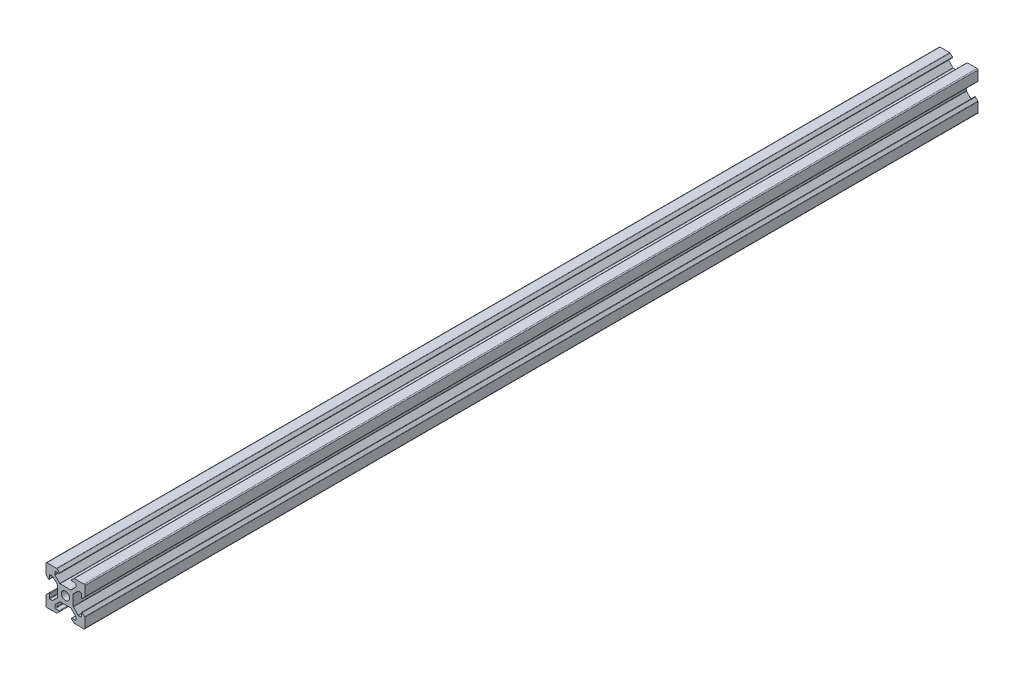
SolidWorks part; units mm, degrees
material "1060 Alloy"
ref_plane "Front Plane" through (0, 0, 0) normal (0, 0, 1) x (1, 0, 0)
ref_plane "Top Plane" through (0, 0, 0) normal (0, 1, 0) x (1, 0, 0)
ref_plane "Right Plane" through (0, 0, 0) normal (1, 0, 0) x (0, 0, -1)
sketch "Model" plane through (0, 0, 0) normal (0, 0, 1) x (1, 0, 0)
  line L0 (2012.9312, 1381.8004) -> (2012.9312, 1378.2004)
  line L1 (2016.4702, 1376.0004) -> (2017.3922, 1376.0004)
  line L2 (2020.9312, 1380.4614) -> (2020.9312, 1379.5394)
  line L3 (2016.4702, 1384.0004) -> (2017.3922, 1384.0004)
  line L270 (2012.9312, 1381.8004) -> (2012.9312, 1382.7004)
  line L271 (2012.8433, 1382.9125) -> (2010.3787, 1385.3772)
  line L272 (2010.2019, 1385.4504) -> (2008.8812, 1385.4504)
  line L273 (2008.6312, 1385.2004) -> (2008.6312, 1383.3504)
  line L274 (2008.2044, 1383.1736) -> (2007.0191, 1384.359)
  line L275 (2006.9312, 1384.5711) -> (2006.9312, 1389.5004)
  line L276 (2007.4312, 1390.0004) -> (2012.3605, 1390.0004)
  line L277 (2012.5726, 1389.9125) -> (2013.758, 1388.7272)
  line L278 (2013.5812, 1388.3004) -> (2011.7312, 1388.3004)
  line L279 (2011.4812, 1388.0504) -> (2011.4812, 1386.7297)
  line L280 (2011.5544, 1386.5529) -> (2014.0338, 1384.0736)
  line L281 (2014.2105, 1384.0004) -> (2016.4702, 1384.0004)
  line L282 (2017.3922, 1384.0004) -> (2019.6519, 1384.0004)
  line L283 (2019.8287, 1384.0736) -> (2022.308, 1386.5529)
  line L284 (2022.3812, 1386.7297) -> (2022.3812, 1388.0504)
  line L285 (2022.1312, 1388.3004) -> (2020.2812, 1388.3004)
  line L286 (2020.1044, 1388.7272) -> (2021.2898, 1389.9125)
  line L287 (2021.5019, 1390.0004) -> (2026.4312, 1390.0004)
  line L288 (2026.9312, 1389.5004) -> (2026.9312, 1384.5711)
  line L289 (2026.8433, 1384.359) -> (2025.658, 1383.1736)
  line L290 (2025.2312, 1383.3504) -> (2025.2312, 1385.2004)
  line L291 (2024.9812, 1385.4504) -> (2023.6605, 1385.4504)
  line L292 (2023.4838, 1385.3772) -> (2021.0044, 1382.8978)
  line L293 (2020.9312, 1382.7211) -> (2020.9312, 1380.4614)
  line L294 (2020.9312, 1379.5394) -> (2020.9312, 1377.2797)
  line L295 (2021.0044, 1377.1029) -> (2023.4838, 1374.6236)
  line L296 (2023.6605, 1374.5504) -> (2024.9812, 1374.5504)
  line L297 (2025.2312, 1374.8004) -> (2025.2312, 1376.6504)
  line L298 (2025.658, 1376.8272) -> (2026.8433, 1375.6418)
  line L299 (2026.9312, 1375.4297) -> (2026.9312, 1370.5004)
  line L300 (2026.4312, 1370.0004) -> (2021.5019, 1370.0004)
  line L301 (2021.2898, 1370.0883) -> (2020.1044, 1371.2736)
  line L302 (2020.2812, 1371.7004) -> (2022.1312, 1371.7004)
  line L303 (2022.3812, 1371.9504) -> (2022.3812, 1373.2711)
  line L304 (2022.308, 1373.4478) -> (2019.8287, 1375.9272)
  line L305 (2019.6519, 1376.0004) -> (2017.3922, 1376.0004)
  line L306 (2016.4702, 1376.0004) -> (2014.2105, 1376.0004)
  line L307 (2014.0338, 1375.9272) -> (2011.5544, 1373.4478)
  line L308 (2011.4812, 1373.2711) -> (2011.4812, 1371.9504)
  line L309 (2011.7312, 1371.7004) -> (2013.5812, 1371.7004)
  line L310 (2013.758, 1371.2736) -> (2012.5726, 1370.0883)
  line L311 (2012.3605, 1370.0004) -> (2007.4312, 1370.0004)
  line L312 (2006.9312, 1370.5004) -> (2006.9312, 1375.4297)
  line L313 (2007.0191, 1375.6418) -> (2008.2044, 1376.8272)
  line L314 (2008.6312, 1376.6504) -> (2008.6312, 1374.8004)
  line L315 (2008.8812, 1374.5504) -> (2010.2019, 1374.5504)
  line L316 (2010.3787, 1374.6236) -> (2012.8433, 1377.0883)
  line L317 (2012.9312, 1377.3004) -> (2012.9312, 1378.2004)
  circle A0 centre (2016.9312, 1380.0004) radius 2.1
  arc A427 (2012.9312, 1382.7004) -> (2012.8433, 1382.9125) centre (2012.6312, 1382.7004) ccw
  arc A428 (2010.3787, 1385.3772) -> (2010.2019, 1385.4504) centre (2010.2019, 1385.2004) ccw
  arc A429 (2008.8812, 1385.4504) -> (2008.6312, 1385.2004) centre (2008.8812, 1385.2004) ccw
  arc A430 (2008.2044, 1383.1736) -> (2008.6312, 1383.3504) centre (2008.3812, 1383.3504) ccw
  arc A431 (2006.9312, 1384.5711) -> (2007.0191, 1384.359) centre (2007.2312, 1384.5711) ccw
  arc A432 (2007.4312, 1390.0004) -> (2006.9312, 1389.5004) centre (2007.4312, 1389.5004) ccw
  arc A433 (2012.5726, 1389.9125) -> (2012.3605, 1390.0004) centre (2012.3605, 1389.7004) ccw
  arc A434 (2013.5812, 1388.3004) -> (2013.758, 1388.7272) centre (2013.5812, 1388.5504) ccw
  arc A435 (2011.7312, 1388.3004) -> (2011.4812, 1388.0504) centre (2011.7312, 1388.0504) ccw
  arc A436 (2011.4812, 1386.7297) -> (2011.5544, 1386.5529) centre (2011.7312, 1386.7297) ccw
  arc A437 (2014.0338, 1384.0736) -> (2014.2105, 1384.0004) centre (2014.2105, 1384.2504) ccw
  arc A441 (2019.6519, 1384.0004) -> (2019.8287, 1384.0736) centre (2019.6519, 1384.2504) ccw
  arc A442 (2022.308, 1386.5529) -> (2022.3812, 1386.7297) centre (2022.1312, 1386.7297) ccw
  arc A443 (2022.3812, 1388.0504) -> (2022.1312, 1388.3004) centre (2022.1312, 1388.0504) ccw
  arc A444 (2020.1044, 1388.7272) -> (2020.2812, 1388.3004) centre (2020.2812, 1388.5504) ccw
  arc A445 (2021.5019, 1390.0004) -> (2021.2898, 1389.9125) centre (2021.5019, 1389.7004) ccw
  arc A446 (2026.9312, 1389.5004) -> (2026.4312, 1390.0004) centre (2026.4312, 1389.5004) ccw
  arc A447 (2026.8433, 1384.359) -> (2026.9312, 1384.5711) centre (2026.6312, 1384.5711) ccw
  arc A448 (2025.2312, 1383.3504) -> (2025.658, 1383.1736) centre (2025.4812, 1383.3504) ccw
  arc A449 (2025.2312, 1385.2004) -> (2024.9812, 1385.4504) centre (2024.9812, 1385.2004) ccw
  arc A450 (2023.6605, 1385.4504) -> (2023.4838, 1385.3772) centre (2023.6605, 1385.2004) ccw
  arc A451 (2021.0044, 1382.8978) -> (2020.9312, 1382.7211) centre (2021.1812, 1382.7211) ccw
  arc A455 (2020.9312, 1377.2797) -> (2021.0044, 1377.1029) centre (2021.1812, 1377.2797) ccw
  arc A456 (2023.4838, 1374.6236) -> (2023.6605, 1374.5504) centre (2023.6605, 1374.8004) ccw
  arc A457 (2024.9812, 1374.5504) -> (2025.2312, 1374.8004) centre (2024.9812, 1374.8004) ccw
  arc A458 (2025.658, 1376.8272) -> (2025.2312, 1376.6504) centre (2025.4812, 1376.6504) ccw
  arc A459 (2026.9312, 1375.4297) -> (2026.8433, 1375.6418) centre (2026.6312, 1375.4297) ccw
  arc A460 (2026.4312, 1370.0004) -> (2026.9312, 1370.5004) centre (2026.4312, 1370.5004) ccw
  arc A461 (2021.2898, 1370.0883) -> (2021.5019, 1370.0004) centre (2021.5019, 1370.3004) ccw
  arc A462 (2020.2812, 1371.7004) -> (2020.1044, 1371.2736) centre (2020.2812, 1371.4504) ccw
  arc A463 (2022.1312, 1371.7004) -> (2022.3812, 1371.9504) centre (2022.1312, 1371.9504) ccw
  arc A464 (2022.3812, 1373.2711) -> (2022.308, 1373.4478) centre (2022.1312, 1373.2711) ccw
  arc A465 (2019.8287, 1375.9272) -> (2019.6519, 1376.0004) centre (2019.6519, 1375.7504) ccw
  arc A469 (2014.2105, 1376.0004) -> (2014.0338, 1375.9272) centre (2014.2105, 1375.7504) ccw
  arc A470 (2011.5544, 1373.4478) -> (2011.4812, 1373.2711) centre (2011.7312, 1373.2711) ccw
  arc A471 (2011.4812, 1371.9504) -> (2011.7312, 1371.7004) centre (2011.7312, 1371.9504) ccw
  arc A472 (2013.758, 1371.2736) -> (2013.5812, 1371.7004) centre (2013.5812, 1371.4504) ccw
  arc A473 (2012.3605, 1370.0004) -> (2012.5726, 1370.0883) centre (2012.3605, 1370.3004) ccw
  arc A474 (2006.9312, 1370.5004) -> (2007.4312, 1370.0004) centre (2007.4312, 1370.5004) ccw
  arc A475 (2007.0191, 1375.6418) -> (2006.9312, 1375.4297) centre (2007.2312, 1375.4297) ccw
  arc A476 (2008.6312, 1376.6504) -> (2008.2044, 1376.8272) centre (2008.3812, 1376.6504) ccw
  arc A477 (2008.6312, 1374.8004) -> (2008.8812, 1374.5504) centre (2008.8812, 1374.8004) ccw
  arc A478 (2010.2019, 1374.5504) -> (2010.3787, 1374.6236) centre (2010.2019, 1374.8004) ccw
  arc A479 (2012.8433, 1377.0883) -> (2012.9312, 1377.3004) centre (2012.6312, 1377.3004) ccw
extrude "Boss-Extrude1" add sketch "Model" along normal blind 460
